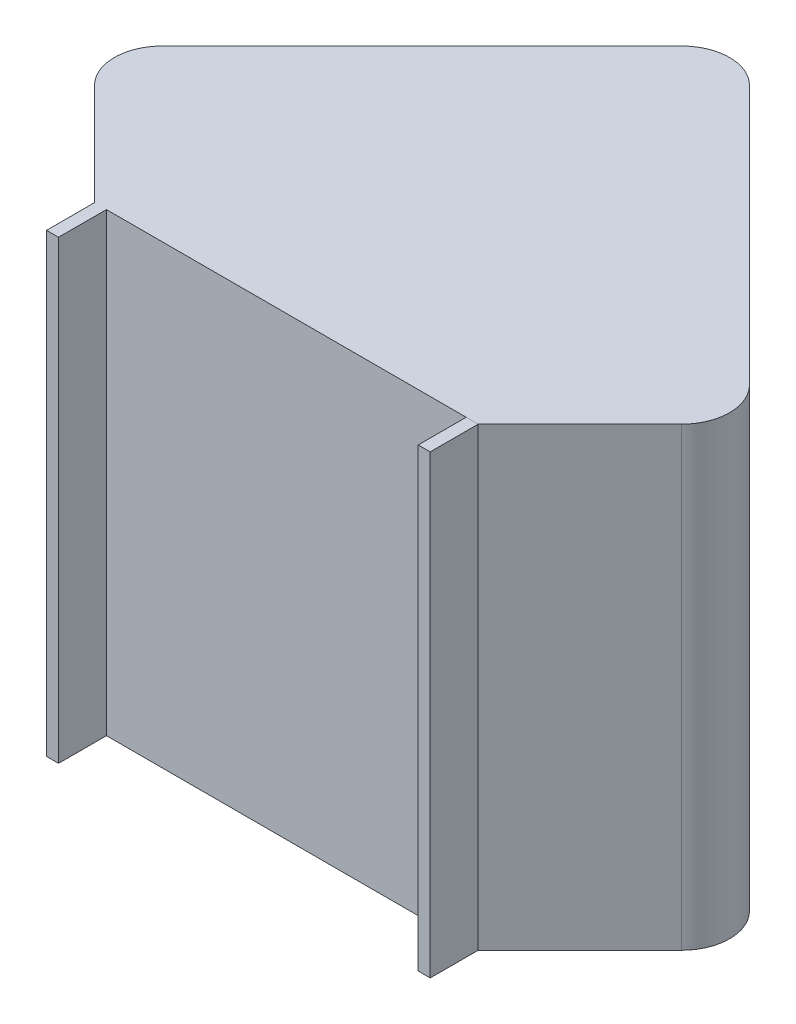
SolidWorks part; units mm, degrees
ref_plane "Front Plane" through (0, 0, 0) normal (0, 0, 1) x (1, 0, 0)
ref_plane "Top Plane" through (0, 0, 0) normal (0, 1, 0) x (1, 0, 0)
ref_plane "Right Plane" through (0, 0, 0) normal (1, 0, 0) x (0, 0, -1)
sketch "Sketch6" plane through (0, 0, 0) normal (0, -1, 0) x (1, 0, 0)
  line L1 (-203.2, 0) -> (-196.85, 0)
  line L2 (-203.2, 0) -> (-203.2, 25.4)
  line L3 (-203.2, 25.4) -> (-196.85, 25.4)
  line L4 (-196.85, 0) -> (-196.85, 25.4)
  line L5 (0, 0) -> (-6.35, 0)
  line L6 (0, 0) -> (0, 25.4)
  line L7 (0, 25.4) -> (-6.35, 25.4)
  line L8 (-6.35, 0) -> (-6.35, 25.4)
  dimension "D1" = 25.4
  dimension "D2" = 6.35
  dimension "D3" = 25.4
  dimension "D4" = 6.35
extrude "Boss-Extrude1" add sketch "Sketch6" against normal blind 241.3
sketch "Sketch9" plane through (-203.2, 0, 0) normal (-1, 0, 0) x (0, 0, 1)
  line L0 (0, 241.3) -> (0, 0) construction
  line L1 (0, 25.4) -> (25.4, 25.4)
  line L2 (0, 25.4) -> (0, 50.9019)
  line L3 (0, 50.9019) -> (25.4, 50.9019)
  line L4 (25.4, 25.4) -> (25.4, 50.9019)
  line L5 (25.4, 241.3) -> (25.4, 0) construction
  line L6 (25.4, 0) -> (0, 0) construction
  line L7 (25.4, 241.3) -> (0, 241.3) construction
  line L8 (0, 76.3019) -> (25.4, 76.3019)
  line L9 (0, 76.3019) -> (0, 101.7019)
  line L10 (0, 101.7019) -> (25.4, 101.7019)
  line L11 (25.4, 76.3019) -> (25.4, 101.7019)
  line L12 (0, 127.1019) -> (25.4, 127.1019)
  line L13 (0, 127.1019) -> (0, 152.5019)
  line L14 (0, 152.5019) -> (25.4, 152.5019)
  line L15 (25.4, 127.1019) -> (25.4, 152.5019)
  line L16 (0, 177.9019) -> (25.4, 177.9019)
  line L17 (0, 177.9019) -> (0, 203.3019)
  line L18 (0, 203.3019) -> (25.4, 203.3019)
  line L19 (25.4, 177.9019) -> (25.4, 203.3019)
  line L20 (0, 228.7019) -> (25.4, 228.7019)
  line L21 (0, 228.7019) -> (0, 241.3)
  line L22 (0, 241.3) -> (25.4, 241.3)
  line L23 (25.4, 228.7019) -> (25.4, 241.3)
  dimension "D1" = 25.4
  dimension "D2" = 25.5019
  dimension "D3" = 25.4
  dimension "D4" = 25.4
  dimension "D5" = 25.4
  dimension "D6" = 25.4
  dimension "D7" = 25.4
  dimension "D8" = 25.4
  dimension "D9" = 25.4
sketch "Sketch10" plane through (0, 0, 0) normal (0, 1, 0) x (1, 0, 0)
  line L0 (0, 0) -> (-203.2, 0)
  line L1 (-203.2, 0) -> (-275.042, 71.842)
  line L2 (-275.042, 71.842) -> (-101.6, 245.2841)
  line L3 (-101.6, 245.2841) -> (71.842, 71.842)
  line L4 (71.842, 71.842) -> (0, 0)
  point P4 (0, 0)
  dimension "D1" = 101.6
  dimension "D2" = 101.6
extrude "Boss-Extrude2" add sketch "Sketch10" along normal blind 241.3
fillet "Fillet2" radius 25.4 1 edges at (-101.6, 120.65, -245.2841)
fillet "Fillet3" radius 25.4 1 edges at (-275.042, 120.65, -71.842)
fillet "Fillet4" radius 25.4 1 edges at (71.842, 120.65, -71.842)
